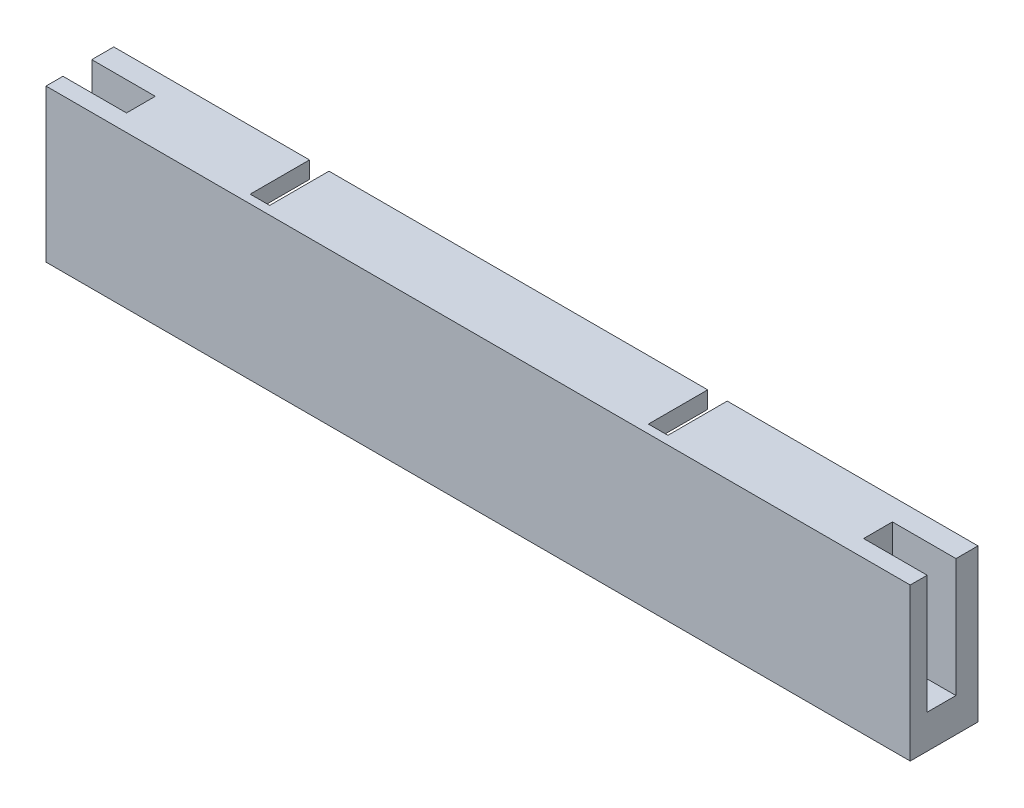
SolidWorks part; units mm, degrees
ref_plane "Front Plane" through (0, 0, 0) normal (0, 0, 1) x (1, 0, 0)
ref_plane "Top Plane" through (0, 0, 0) normal (0, 1, 0) x (1, 0, 0)
ref_plane "Right Plane" through (0, 0, 0) normal (1, 0, 0) x (0, 0, -1)
sketch "Sketch1" plane through (0, 0, 0) normal (0, 0, 1) x (1, 0, 0)
  line L1 (-51, -9) -> (51, -9)
  line L2 (-51, -9) -> (-51, 9)
  line L3 (-51, 9) -> (51, 9)
  line L4 (51, -9) -> (51, 9)
  line L5 (-51, -9) -> (51, 9) construction
  line L6 (-51, 9) -> (51, -9) construction
  point P0 (0, 0)
  dimension "D1" = 102
  dimension "D2" = 18
extrude "Boss-Extrude1" add sketch "Sketch1" along normal blind 2
sketch "Sketch2" plane through (0, 9, 0) normal (0, 1, 0) x (1, 0, 0)
  line L0 (0, -2) -> (0, 15.0089) construction
  line L1 (-51, -2) -> (-40.5, -2)
  line L2 (-51, -2) -> (-51, 6)
  line L3 (-51, 6) -> (-40.5, 6)
  line L4 (-40.5, -2) -> (-40.5, 6)
  line L5 (-51, 0) -> (-43.5, 0)
  line L6 (-51, 0) -> (-51, 3.4)
  line L7 (-51, 3.4) -> (-43.5, 3.4)
  line L8 (-43.5, 0) -> (-43.5, 3.4)
  line L9 (51, -2) -> (-51, -2) construction
  line L10 (43.5, 0) -> (43.5, 3.4)
  line L11 (51, 3.4) -> (43.5, 3.4)
  line L12 (51, 0) -> (51, 3.4)
  line L13 (51, 0) -> (43.5, 0)
  line L14 (40.5, -2) -> (40.5, 6)
  line L15 (51, 6) -> (40.5, 6)
  line L16 (51, -2) -> (51, 6)
  line L17 (51, -2) -> (40.5, -2)
  line M8 (51, 0) -> (-51, 0)
  dimension "D1" = 8
  dimension "D2" = 10.5
  dimension "D3" = 3.4
  dimension "D4" = 7.5
extrude "Boss-Extrude2" add sketch "Sketch2" against normal blind 18 contours L8 L4 L3 L2 L7 M8 | L11 L16 L15 L14 L10 M8
sketch "Sketch4" plane through (0, 0, 0) normal (0, 0, -1) x (-1, 0, 0)
  line L0 (40.5, -9) -> (40.5, 9) construction
  line L1 (-40.5, 9) -> (40.5, 9)
  line L2 (-40.5, 9) -> (-40.5, 7)
  line L3 (-40.5, 7) -> (40.5, 7)
  line L4 (40.5, 9) -> (40.5, 7)
  line L5 (40.5, -9) -> (40.5, 9) construction
  line L6 (-40.5, -9) -> (40.5, -9)
  line L7 (-40.5, -9) -> (-40.5, -7)
  line L8 (-40.5, -7) -> (40.5, -7)
  line L9 (40.5, -9) -> (40.5, -7)
  dimension "D1" = 2
  dimension "D2" = 2
extrude "Boss-Extrude3" add sketch "Sketch4" along normal blind 6
sketch "Sketch5" plane through (0, 0, -6) normal (0, 0, -1) x (-1, 0, 0)
  line L0 (40.5, -7) -> (-40.5, -7) construction
  line L1 (25.6, -7) -> (27.9, -7)
  line L2 (25.6, -7) -> (25.6, -9)
  line L3 (25.6, -9) -> (27.9, -9)
  line L4 (27.9, -7) -> (27.9, -9)
  line L5 (51, -9) -> (-51, -9) construction
  line L6 (51, -9) -> (51, 9) construction
  line L7 (-40.5, 7) -> (40.5, 7) construction
  line L8 (27.9, 7) -> (25.6, 7)
  line L9 (27.9, 7) -> (27.9, 9)
  line L10 (27.9, 9) -> (25.6, 9)
  line L11 (25.6, 7) -> (25.6, 9)
  line L12 (51, 9) -> (-51, 9) construction
  line L13 (-19.1, 7) -> (-19.1, 9)
  line L14 (-19.1, 7) -> (-21.4, 7)
  line L15 (-21.4, 7) -> (-21.4, 9)
  line L16 (-19.1, 9) -> (-21.4, 9)
  line L17 (-21.4, -7) -> (-19.1, -7)
  line L18 (-19.1, -7) -> (-19.1, -9)
  line L19 (-21.4, -9) -> (-19.1, -9)
  line L20 (-21.4, -7) -> (-21.4, -9)
  line L21 (26.75, 7) -> (26.75, -7) construction
  line L22 (-20.25, 7) -> (-20.25, -9) construction
  point P8 (26.75, -7)
  point P29 (26.75, 9)
  point P30 (-20.25, 9)
  point P33 (-20.25, -7)
  dimension "D1" = 2.3
  dimension "D2" = 24.25
  dimension "D4" = 2.3
  dimension "D3" = 2.3
  dimension "D5" = 2.3
  dimension "D6" = 47
  dimension "D7" = 2
  dimension "D8" = 2
extrude "Cut-Extrude1" cut sketch "Sketch5" against normal blind 6
sketch "Sketch8" plane through (0, 0, 0) normal (0, 0, -1) x (-1, 0, 0)
  line L0 (40.5, 0) -> (0, 0) construction
  line L1 (34.75, 3) -> (32.75, 3)
  line L2 (34.75, 3) -> (34.75, -3)
  line L3 (34.75, -3) -> (32.75, -3)
  line L4 (32.75, 3) -> (32.75, -3)
  line L5 (40.5, -7) -> (40.5, 7) construction
  line L6 (25.6, 8) -> (27.9, 8) construction
  line L7 (25.6, 9) -> (25.6, 7) construction
  line L8 (27.9, 7) -> (27.9, 9) construction
  line L9 (26.75, 8) -> (26.75, 0) construction
  line L10 (0, 0) -> (-40.5, 0) construction
  line L11 (-40.5, -7) -> (-40.5, 7) construction
  line L12 (-20.25, -9) -> (-20.25, 0) construction
  line L13 (-21.4, -9) -> (-19.1, -9) construction
  line L14 (-20.25, 0) -> (-20.25, 9) construction
  line L15 (-19.1, 9) -> (-21.4, 9) construction
  line L16 (-12.25, 3) -> (-14.25, 3)
  line L17 (-12.25, 3) -> (-12.25, -3)
  line L18 (-12.25, -3) -> (-14.25, -3)
  line L19 (-14.25, 3) -> (-14.25, -3)
  point P17 (32.75, 0)
  point P33 (-12.25, 0)
  dimension "D1" = 6
  dimension "D2" = 2
  dimension "D3" = 6
  dimension "D4" = 2
  dimension "D5" = 6
  dimension "D6" = 6
extrude "Boss-Extrude5" add sketch "Sketch8" along normal blind 1
sketch "Sketch10" plane through (0, 0, -1) normal (0, 0, -1) x (-1, 0, 0)
  line L0 (-12.25, 3) -> (-15.75, 3)
  line L1 (34.75, 3) -> (31.25, 3)
  line L2 (34.75, 3) -> (34.75, -3)
  line L3 (34.75, -3) -> (31.25, -3)
  line L4 (31.25, 3) -> (31.25, -3)
  line L5 (-12.25, 3) -> (-12.25, -3)
  line L6 (-12.25, -3) -> (-15.75, -3)
  line L7 (-15.75, 3) -> (-15.75, -3)
  line L8 (-12.25, -3) -> (-12.25, 3) construction
  line L9 (-14.25, -3) -> (-12.25, -3) construction
  line L10 (-12.25, 3) -> (-14.25, 3) construction
  dimension "D1" = 3.5
  dimension "D2" = 3.5
extrude "Boss-Extrude6" add sketch "Sketch10" along normal blind 1
sketch "Sketch11" plane through (0, 0, 0) normal (0, 0, -1) x (-1, 0, 0)
  line L0 (0, 0) -> (34.75, 0) construction
  line L1 (34.75, -3) -> (34.75, 3) construction
  line L2 (25.6, 8) -> (27.9, 8) construction
  line L3 (25.6, 9) -> (25.6, 7) construction
  line L4 (27.9, 7) -> (27.9, 9) construction
  line L5 (26.75, 8) -> (26.75, 0) construction
  line L6 (0, 0) -> (-51, 0) construction
  line L7 (5.05, 3) -> (6.55, 3)
  line L8 (5.05, 3) -> (5.05, -3)
  line L9 (5.05, -3) -> (6.55, -3)
  line L10 (6.55, 3) -> (6.55, -3)
  line L11 (-51, -9) -> (-51, 9) construction
  line L12 (-20.25, 9) -> (-20.25, 0) construction
  line L13 (-19.1, 9) -> (-21.4, 9) construction
  line L14 (-41.95, 3) -> (-40.45, 3)
  line L15 (-41.95, 3) -> (-41.95, -3)
  line L16 (-41.95, -3) -> (-40.45, -3)
  line L17 (-40.45, 3) -> (-40.45, -3)
  point P17 (6.55, 0)
  point P29 (-40.45, 0)
  dimension "D1" = 20.2
  dimension "D2" = 1.5
  dimension "D3" = 6
  dimension "D4" = 1.5
  dimension "D5" = 6
  dimension "D6" = 20.2
extrude "Boss-Extrude7" add sketch "Sketch11" along normal blind 8
sketch "Sketch12" plane through (0, -3, 0) normal (0, -1, 0) x (1, 0, 0)
  line L0 (-6.55, -8) -> (-7.55, -6)
  line L1 (-7.55, -6) -> (-6.55, -6)
  line L2 (-6.55, -8) -> (-6.55, 0) construction
  line L3 (-6.55, -8) -> (-6.55, -6)
  line L4 (40.45, -8) -> (39.45, -6)
  line L5 (39.45, -6) -> (40.45, -6)
  line L6 (40.45, -8) -> (40.45, -6)
  line L7 (40.45, -8) -> (40.45, 0) construction
  point P9 (0, 0)
  point P14 (0, 0)
  point P15 (0, 0)
  dimension "D1" = 1
  dimension "D2" = 2
  dimension "D3" = 1
  dimension "D4" = 2
extrude "Boss-Extrude8" add sketch "Sketch12" against normal blind 6
sketch "Sketch17" plane through (0, 0, 0) normal (0, 1, 0) x (1, 0, 0)
  line L0 (-5.05, 8) -> (1.95, 0)
  line L2 (-25.6, 0) -> (19.1, 0) construction
  line L3 (-5.05, 8) -> (-5.05, 0) construction
  dimension "D1" = 7
rib "Rib1" sketch "Sketch17" sketch "Sketch17" thickness 4 extrusion direction parallel to sketch draft on no parameters "D1"=4
chamfer "Chamfer1" distance 0.5 angle 45 2 edges at (-31.25, 0, -1) (15.75, 0, -1)
sketch "Sketch18" plane through (0, -9, 0) normal (0, -1, 0) x (1, 0, 0)
  line L1 (43.5, -3.4) -> (51, -3.4)
  line L2 (43.5, -3.4) -> (43.5, 0)
  line L3 (43.5, 0) -> (51, 0)
  line L4 (51, -3.4) -> (51, 0)
  line L5 (-43.5, -3.4) -> (-51, -3.4)
  line L6 (-43.5, -3.4) -> (-43.5, 0)
  line L7 (-43.5, 0) -> (-51, 0)
  line L8 (-51, -3.4) -> (-51, 0)
extrude "Boss-Extrude10" add sketch "Sketch18" against normal blind 4
sketch "Sketch19" plane through (0, 0, 0) normal (0, 0, -1) x (-1, 0, 0)
  line L0 (6.55, 0) -> (32.7255, 0) construction
  line L1 (6.55, -3) -> (6.55, 3) construction
  line L2 (27.9, 9) -> (25.6, 9) construction
  line L3 (-40.4455, -0.4841) -> (-14.27, -0.4841) construction
  line L4 (6.55, -5.5) -> (32.7255, -5.5)
  line L5 (6.55, -5.5) -> (6.55, 5.5)
  line L6 (6.55, 5.5) -> (32.7255, 5.5)
  line L7 (32.7255, -5.5) -> (32.7255, 5.5)
  line L8 (6.55, -5.5) -> (32.7255, 5.5) construction
  line L9 (6.55, 5.5) -> (32.7255, -5.5) construction
  line L10 (-40.4455, -5.9841) -> (-14.27, -5.9841)
  line L11 (-40.4455, -5.9841) -> (-40.4455, 5.0159)
  line L12 (-40.4455, 5.0159) -> (-14.27, 5.0159)
  line L13 (-14.27, -5.9841) -> (-14.27, 5.0159)
  line L14 (-40.4455, -5.9841) -> (-14.27, 5.0159) construction
  line L15 (-40.4455, 5.0159) -> (-14.27, -5.9841) construction
  line L16 (-19.1, 9) -> (-21.4, 9) construction
  point P5 (19.6377, 0)
  point P11 (26.75, 9)
  point P14 (-27.3577, -0.4841)
  point P21 (-20.25, 9)
  dimension "D1" = 11
  dimension "D2" = 5.9755
  dimension "D3" = 11
  dimension "D4" = 5.98
extrude "Cut-Extrude3" cut sketch "Sketch19" against normal blind 1
sketch "Sketch20" plane through (0, 9, 0) normal (0, 1, 0) x (1, 0, 0)
  line L0 (-27.9, 0) -> (-25.6, 0)
  line L1 (-25.6, 0) -> (-25.6, -1)
  line L2 (-25.6, -1) -> (-27.9, -1)
  line L3 (-27.9, -1) -> (-27.9, 0)
  line L4 (21.4, 0) -> (21.4, 6) construction
  line L5 (19.1, 0) -> (21.4, 0)
  line L6 (19.1, 0) -> (19.1, -1)
  line L7 (19.1, -1) -> (21.4, -1)
  line L8 (21.4, 0) -> (21.4, -1)
  dimension "D1" = 1
  dimension "D2" = 1
extrude "Cut-Extrude4" cut sketch "Sketch20" against normal blind 18
